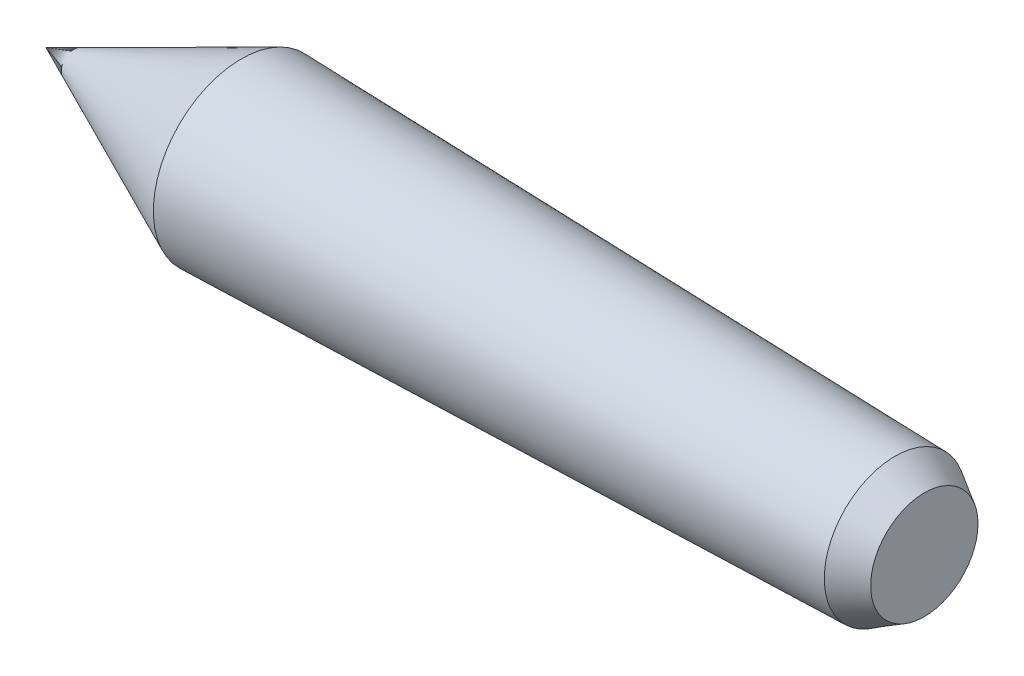
SolidWorks part; units mm, degrees
ref_plane "Front Plane" through (0, 0, 0) normal (0, 0, 1) x (1, 0, 0)
ref_plane "Top Plane" through (0, 0, 0) normal (0, 1, 0) x (1, 0, 0)
ref_plane "Right Plane" through (0, 0, 0) normal (1, 0, 0) x (0, 0, -1)
sketch "Sketch1" plane through (0, 0, 0) normal (0, 0, 1) x (1, 0, 0)
  line L0 (0, 0) -> (20, 9)
  line L1 (20, 9) -> (87, 7.25)
  line L2 (87, 7.25) -> (90, 5.5)
  line L3 (90, 5.5) -> (90, 0)
  line L4 (90, 0) -> (0, 0)
  point P3 (0, 0)
  dimension "D1" = 90
  dimension "D2" = 9
  dimension "D3" = 20
  dimension "D4" = 5.5
  dimension "D5" = 7.25
  dimension "D6" = 3
revolve "Revolve2" add sketch "Sketch1" angle 360 about L4
